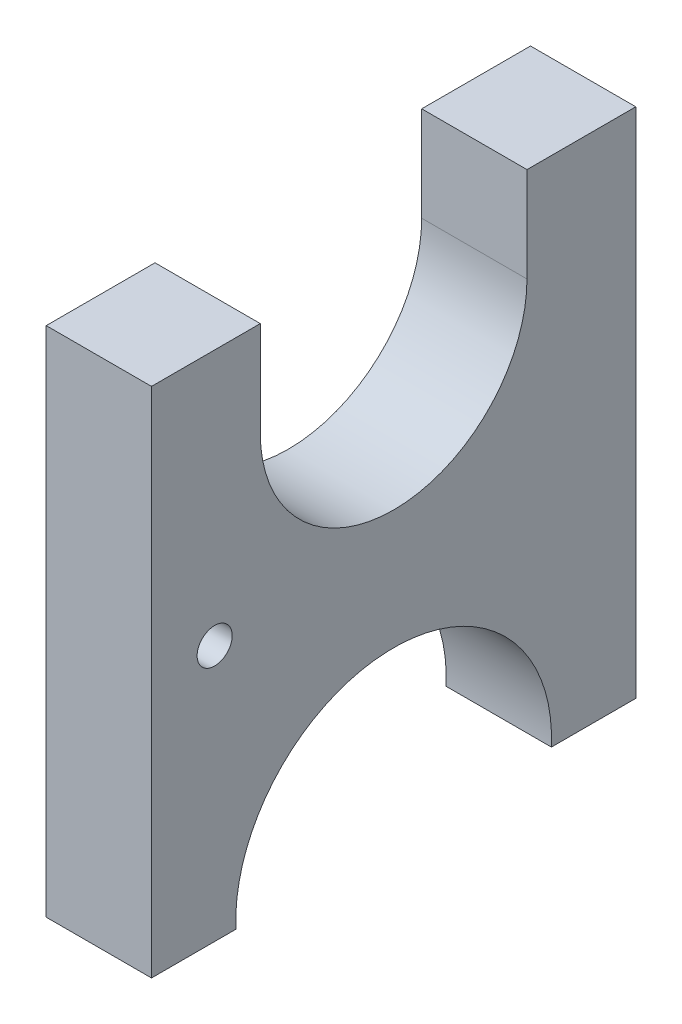
SolidWorks part; units mm, degrees
material "2014 Alloy"
ref_plane "Front Plane" through (0, 0, 0) normal (0, 0, 1) x (1, 0, 0)
ref_plane "Top Plane" through (0, 0, 0) normal (0, 1, 0) x (1, 0, 0)
ref_plane "Right Plane" through (0, 0, 0) normal (1, 0, 0) x (0, 0, -1)
sketch "Sketch1" plane through (0, 0, 0) normal (1, 0, 0) x (0, 0, -1)
  line L0 (-33.5, 0) -> (33.5, 0)
  line L1 (33.5, 0) -> (33.5, -71)
  line L2 (33.5, -71) -> (23.5, -71)
  line L3 (0, 0) -> (0, -71) construction
  line L4 (-33.5, -71) -> (-23.5, -71)
  line L5 (-33.5, 0) -> (-33.5, -71)
  arc A0 (23.5, -71) -> (-23.5, -71) centre (0, -71) ccw
  dimension "D1" = 71
  dimension "D3" = 23.5
  dimension "D2" = 10
extrude "Boss-Extrude1" add sketch "Sketch1" along normal blind 12
hole_wizard "M5 Tapped Hole1" positions "Sketch3" profile "Sketch2" tap size "M5" standard "ISO"
sketch "Sketch3" plane through (0, -71, 0) normal (0, -1, 0) x (-1, 0, 0)
  line L0 (-6, -33.5) -> (-6, -23.5) construction
  line L1 (-12, -33.5) -> (0, -33.5) construction
  line L2 (-12, -23.5) -> (0, -23.5) construction
  line L3 (-6, -23.5) -> (-6, 23.5) construction
  line L4 (-12, 23.5) -> (0, 23.5) construction
  line L5 (-6, 23.5) -> (-6, 33.5) construction
  line L6 (-12, 33.5) -> (0, 33.5) construction
  point P0 (-6, -28.5)
  point P2 (-6, 28.5)
sketch "Sketch2" plane through (6, -71, 28.5) normal (1, 0, 0) x (0, 0, -1)
  line L0 (0, 0) -> (0, 15.2618)
  line L1 (0, 15.2618) -> (2.1, 14)
  line L2 (2.1, 14) -> (2.1, 0.425)
  line L3 (2.1, 0.425) -> (2.525, 0)
  line L5 (2.525, 0) -> (0, 0)
  line L6 (-2.1, 0.425) -> (-2.525, 0) construction
  line L10 (0, 15.2618) -> (-2.1, 14) construction
  line L11 (0, -6.35) -> (0, 107.95) construction
  dimension "Tap Drill Dia." = 4.2
  dimension "Tap Drill Depth" = 14
  dimension "Near C'Sink Dia." = 5.05
  dimension "Near C'Sink Angle" = 90
  dimension "Drill Angle" = 118
hole_wizard "M5 Tapped Hole2" positions "Sketch5" profile "Sketch4" tap size "M5" standard "ISO"
sketch "Sketch5" plane through (0, 0, 0) normal (0, 1, 0) x (1, 0, 0)
  line L0 (6, -33.5) -> (6, -27.5) construction
  line L1 (12, -33.5) -> (0, -33.5) construction
  line L2 (6, -27.5) -> (6, 27.5) construction
  line L3 (6, 27.5) -> (6, 33.5) construction
  line L4 (12, 33.5) -> (0, 33.5) construction
  line L5 (6, 33.5) -> (12, 27.5) construction
  line L6 (12, 33.5) -> (12, -33.5) construction
  line L7 (12, 27.5) -> (6, 27.5) construction
  point P0 (6, -27.5)
  point P2 (6, 27.5)
  dimension "D1" = 6
sketch "Sketch4" plane through (6, 0, 27.5) normal (1, 0, 0) x (0, 0, 1)
  line L0 (0, 0) -> (0, 18.7618)
  line L1 (0, 18.7618) -> (2.1, 17.5)
  line L2 (2.1, 17.5) -> (2.1, 0.425)
  line L3 (2.1, 0.425) -> (2.525, 0)
  line L5 (2.525, 0) -> (0, 0)
  line L6 (-2.1, 0.425) -> (-2.525, 0) construction
  line L10 (0, 18.7618) -> (-2.1, 17.5) construction
  line L11 (0, -6.35) -> (0, 107.95) construction
  dimension "Tap Drill Dia." = 4.2
  dimension "Tap Drill Depth" = 17.5
  dimension "Near C'Sink Dia." = 5.05
  dimension "Near C'Sink Angle" = 90
  dimension "Drill Angle" = 118
sketch "Sketch6" plane through (12, 0, 0) normal (1, 0, 0) x (0, 0, -1)
  line L0 (0, 12.5) -> (0, -12.5) construction
  line L1 (33.5, 0) -> (-33.5, 0) construction
  line L2 (20, 12.5) -> (20, -12.5)
  line L3 (-20, 12.5) -> (-20, -12.5)
  arc A0 (20, 12.5) -> (-20, 12.5) centre (0, 12.5) ccw
  arc A1 (-20, -12.5) -> (20, -12.5) centre (0, -12.5) ccw
  point P4 (0, 0)
  dimension "D1" = 20
  dimension "D2" = 25
extrude "Cut-Extrude1" cut sketch "Sketch6" against normal through all
sketch "Sketch7" plane through (12, 0, 0) normal (1, 0, 0) x (0, 0, -1)
  line L0 (-33.5, 0) -> (-33.5, -71) construction
  line L1 (-33.5, -35.5) -> (-25.5, -35.5) construction
  circle A0 centre (-25.5, -35.5) radius 2.5
  dimension "D1" = 5
  dimension "D2" = 8
extrude "Cut-Extrude2" cut sketch "Sketch7" against normal through all
sketch "Sketch8" plane through (12, 0, 0) normal (1, 0, 0) x (0, 0, -1)
  line L0 (-19, 1) -> (-34.5, 1)
  line L1 (-34.5, 1) -> (-34.5, -72)
  line L2 (-34.5, -72) -> (-22.4778, -72)
  line L3 (22.4778, -72) -> (34.5, -72)
  line L4 (34.5, -72) -> (34.5, 1)
  line L5 (34.5, 1) -> (19, 1)
  line L6 (19, 1) -> (19, -12.5)
  line L7 (-19, -12.5) -> (-19, 1)
  line L8 (20, 0) -> (20, -12.5)
  line L9 (-20, -12.5) -> (-20, 0)
  line L10 (-20, 0) -> (-33.5, 0)
  line L11 (-33.5, 0) -> (-33.5, -71)
  line L12 (-33.5, -71) -> (-23.5, -71)
  line L13 (23.5, -71) -> (33.5, -71)
  line L14 (33.5, -71) -> (33.5, 0)
  line L15 (33.5, 0) -> (20, 0)
  line L16 (20, 0) -> (20, -12.5) construction
  line L17 (-20, -12.5) -> (-20, 0) construction
  line L18 (-20, 0) -> (-33.5, 0) construction
  line L19 (-33.5, 0) -> (-33.5, -71) construction
  line L20 (-33.5, -71) -> (-23.5, -71) construction
  line L21 (23.5, -71) -> (33.5, -71) construction
  line L22 (33.5, -71) -> (33.5, 0) construction
  line L23 (33.5, 0) -> (20, 0) construction
  circle A0 centre (-25.5, -35.5) radius 2.5 construction
  circle A1 centre (-25.5, -35.5) radius 2.5
  arc A2 (-20, -12.5) -> (20, -12.5) centre (0, -12.5) ccw
  arc A3 (23.5, -71) -> (-23.5, -71) centre (0, -71) ccw
  arc A4 (-20, -12.5) -> (20, -12.5) centre (0, -12.5) ccw construction
  arc A5 (23.5, -71) -> (-23.5, -71) centre (0, -71) ccw construction
  arc A6 (22.4778, -72) -> (-22.4778, -72) centre (0, -71) ccw
  arc A7 (-19, -12.5) -> (19, -12.5) centre (0, -12.5) ccw
  dimension "D1" = 0
  dimension "D2" = 1
extrude "Boss-Extrude2" add sketch "Sketch8" against normal blind 15
